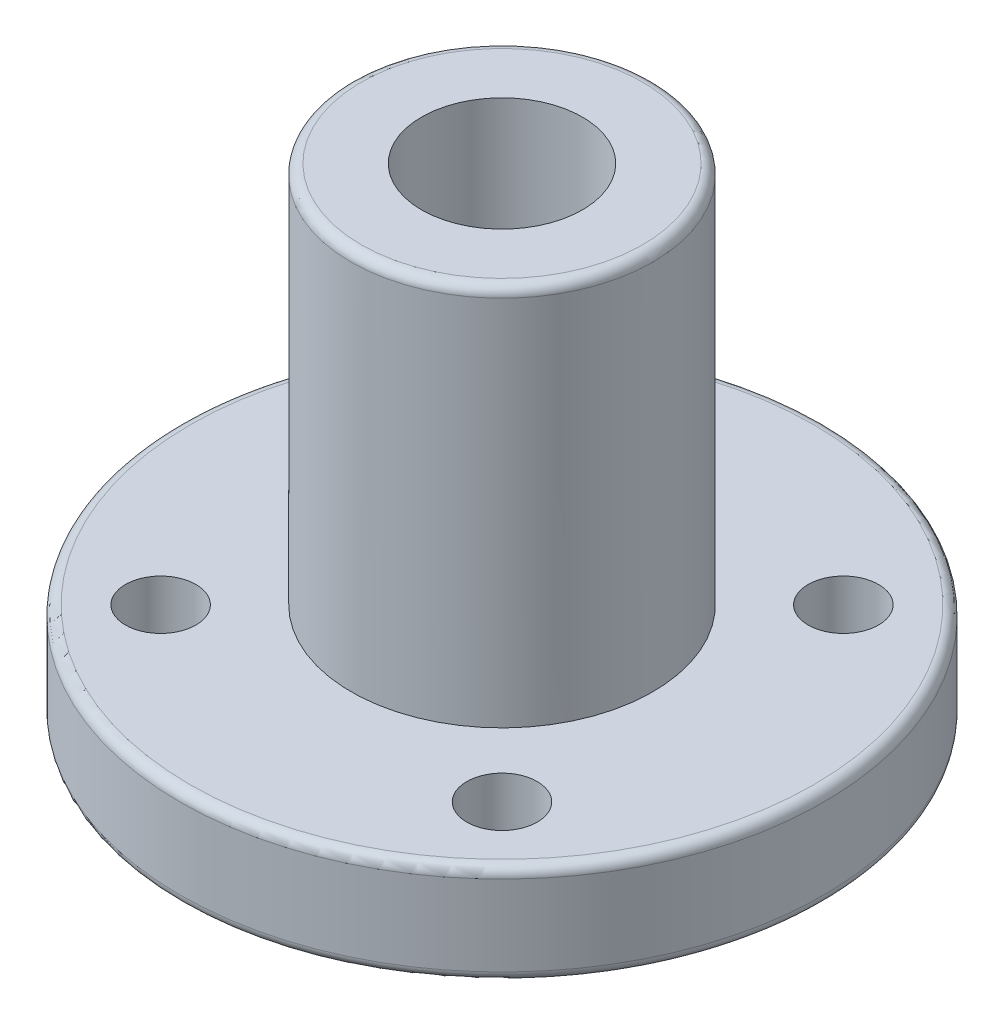
SolidWorks part; units mm, degrees
ref_plane "Front Plane" through (0, 0, 0) normal (0, 0, 1) x (1, 0, 0)
ref_plane "Top Plane" through (0, 0, 0) normal (0, 1, 0) x (1, 0, 0)
ref_plane "Right Plane" through (0, 0, 0) normal (1, 0, 0) x (0, 0, -1)
sketch "Sketch1" plane through (0, 0, 0) normal (0, 1, 0) x (1, 0, 0)
  circle A0 centre (0, 0) radius 7.5
  circle A1 centre (0, 0) radius 4
  dimension "D1" = 8
  dimension "D2" = 15
extrude "Boss-Extrude1" add sketch "Sketch1" along normal blind 24
sketch "Sketch2" plane through (0, 0, 0) normal (0, -1, 0) x (1, 0, 0)
  line L0 (0, 0) -> (0, 11.1142) construction
  line L1 (-12.5, 12.5) -> (12.5, 12.5) construction
  line L2 (-12.5, 12.5) -> (-12.5, -12.5) construction
  line L3 (-12.5, -12.5) -> (12.5, -12.5) construction
  line L4 (12.5, 12.5) -> (12.5, -12.5) construction
  line L5 (0, 0) -> (11.2445, 0) construction
  line L6 (0, 0) -> (8.4853, 8.4853) construction
  circle A0 centre (8.4853, 8.4853) radius 1.75
  circle A1 centre (0, 0) radius 7.5 construction
  circle A2 centre (0, 0) radius 7.5
  circle A3 centre (-8.4853, 8.4853) radius 1.75
  circle A4 centre (-8.4853, -8.4853) radius 1.75
  circle A5 centre (8.4853, -8.4853) radius 1.75
  circle A6 centre (0, 0) radius 16
  circle A7 centre (0, 0) radius 12 construction
  point P8 (-12.5, 0)
  point P9 (0, 12.5)
  dimension "D1" = 25
  dimension "D2" = 3.5
  dimension "D4" = 24
  dimension "D3" = 32
  dimension "D5" = 45
extrude "Boss-Extrude2" add sketch "Sketch2" against normal blind 5
fillet "Fillet2" radius 0.5 3 edges at (0, 0, -16) (0, 24, 7.5) (0, 5, -16)
